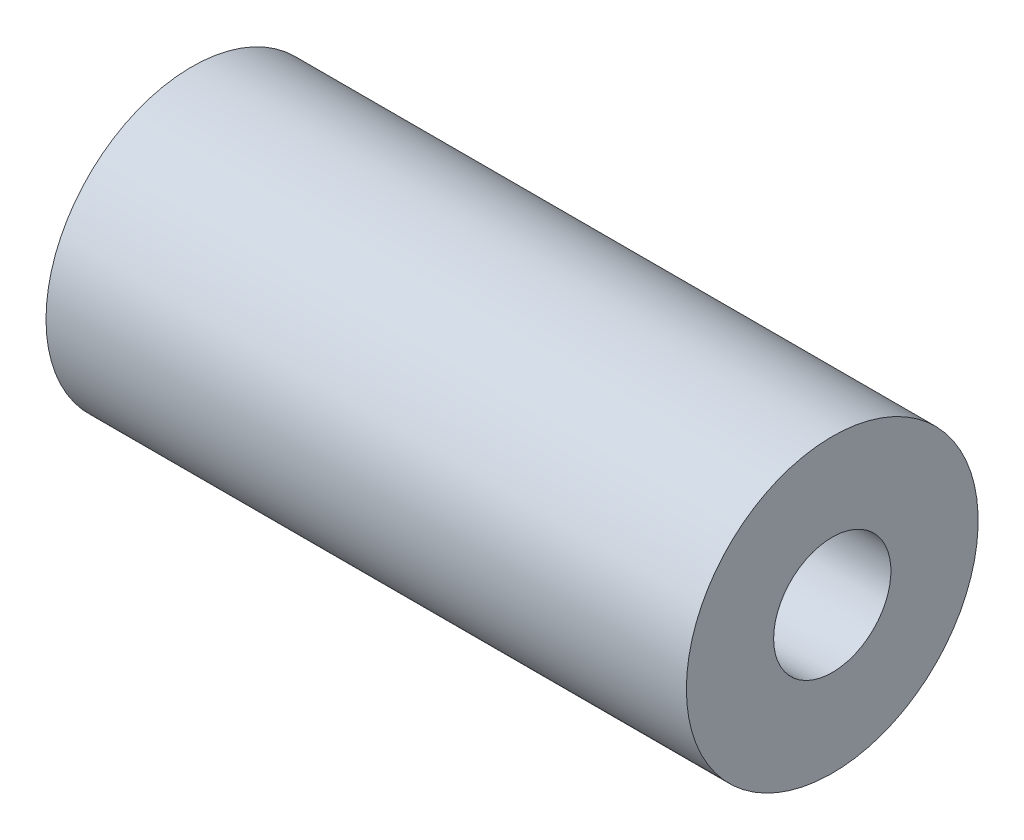
SolidWorks part; units mm, degrees
material "PBT General Purpose"
ref_plane "Front Plane" through (0, 0, 0) normal (0, 0, 1) x (1, 0, 0)
ref_plane "Top Plane" through (0, 0, 0) normal (0, 1, 0) x (1, 0, 0)
ref_plane "Right Plane" through (0, 0, 0) normal (1, 0, 0) x (0, 0, -1)
sketch "Sketch1" plane through (0, 0, 0) normal (1, 0, 0) x (0, 0, -1)
  circle A0 centre (0, 0) radius 2.5527
  circle A1 centre (0, 0) radius 6.35
  dimension "D1" = 5.1054
  dimension "D2" = 12.7
extrude "Boss-Extrude1" add sketch "Sketch1" along normal blind 27.8752
